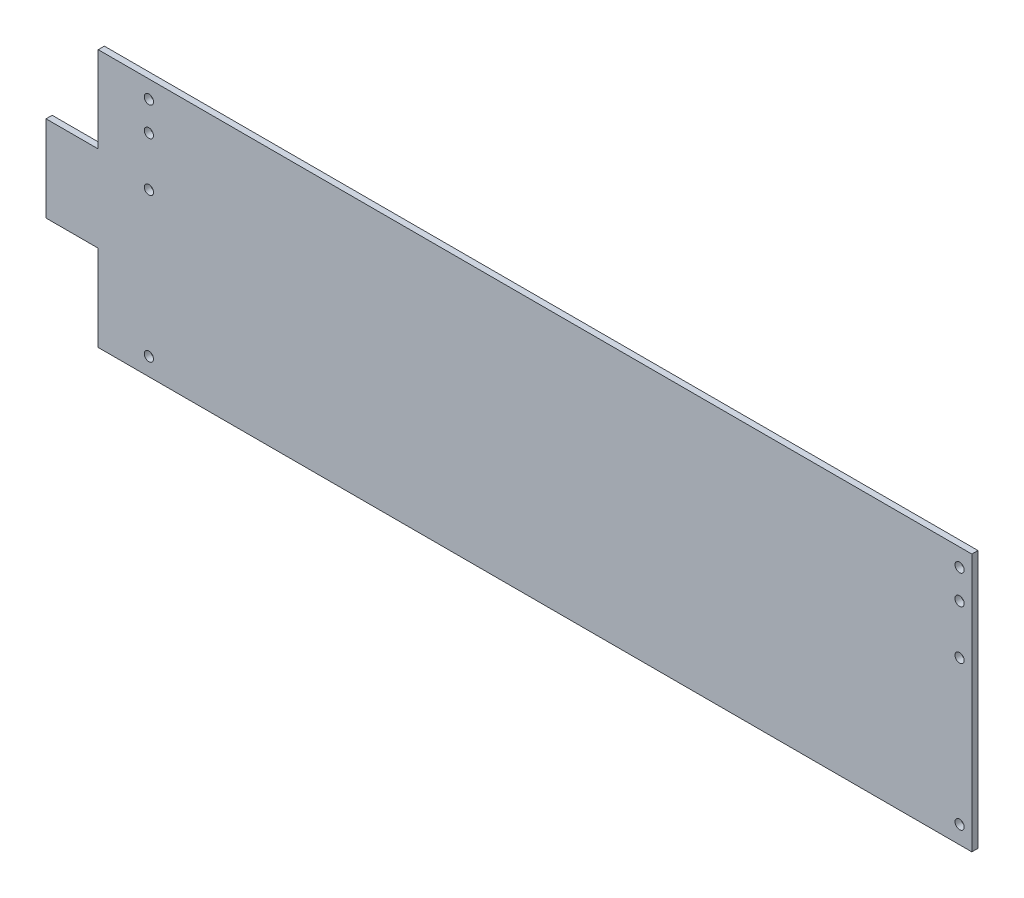
SolidWorks part; units mm, degrees
ref_plane "Front Plane" through (0, 0, 0) normal (0, 0, 1) x (1, 0, 0)
ref_plane "Top Plane" through (0, 0, 0) normal (0, 1, 0) x (1, 0, 0)
ref_plane "Right Plane" through (0, 0, 0) normal (1, 0, 0) x (0, 0, -1)
sketch "Model" plane through (0, 0, 0) normal (0, 0, 1) x (1, 0, 0)
  line L156 (0, 42) -> (0, -42) construction
  line L161 (-136, -42) -> (136, -42)
  line L174 (-136, -42) -> (-136, 42)
  line L179 (-136, 42) -> (136, 42)
  line L192 (136, -42) -> (136, 42)
  line L205 (-136, -42) -> (136, 42) construction
  line L210 (-136, 42) -> (136, -42) construction
  line L240 (-136, 42) -> (-148.5, 42)
  line L253 (-136, 42) -> (-136, -42)
  line L258 (-136, -42) -> (-148.5, -42)
  line L271 (-148.5, 42) -> (-148.5, -42)
  line L320 (-148.5, 14) -> (-165.5, 14)
  line L321 (-148.5, 14) -> (-148.5, -14)
  line L322 (-148.5, -14) -> (-165.5, -14)
  line L323 (-165.5, 14) -> (-165.5, -14)
  circle A8 centre (132, 36.25) radius 1.5
  circle A9 centre (132, 26.75) radius 1.5
  circle A10 centre (132, 10.75) radius 1.5
  circle A11 centre (132, -36.25) radius 1.5
  circle A12 centre (-132, -36.25) radius 1.5
  circle A13 centre (-132, 10.75) radius 1.5
  circle A14 centre (-132, 26.75) radius 1.5
  circle A15 centre (-132, 36.25) radius 1.5
  point P0 (0, 0)
  point P27 (-148.5, 0)
  point P31 (-165.5, 0)
  dimension "D6" = 5.75
  dimension "D3" = 5.75
  dimension "D8" = 3
  dimension "D1" = 272
  dimension "D2" = 84
  dimension "D4" = 9.5
  dimension "D5" = 16
  dimension "D7" = 4
  dimension "D9" = 12.5
  dimension "D10" = 17
  dimension "D11" = 28
extrude "Boss-Extrude1" add sketch "Model" along normal blind 2 contours L161 L192 L179 L174 A14 A12 A11 A10 A9 A8 A13 A15 | L240 L271 L258 L174 | L320 L323 L322 L271
